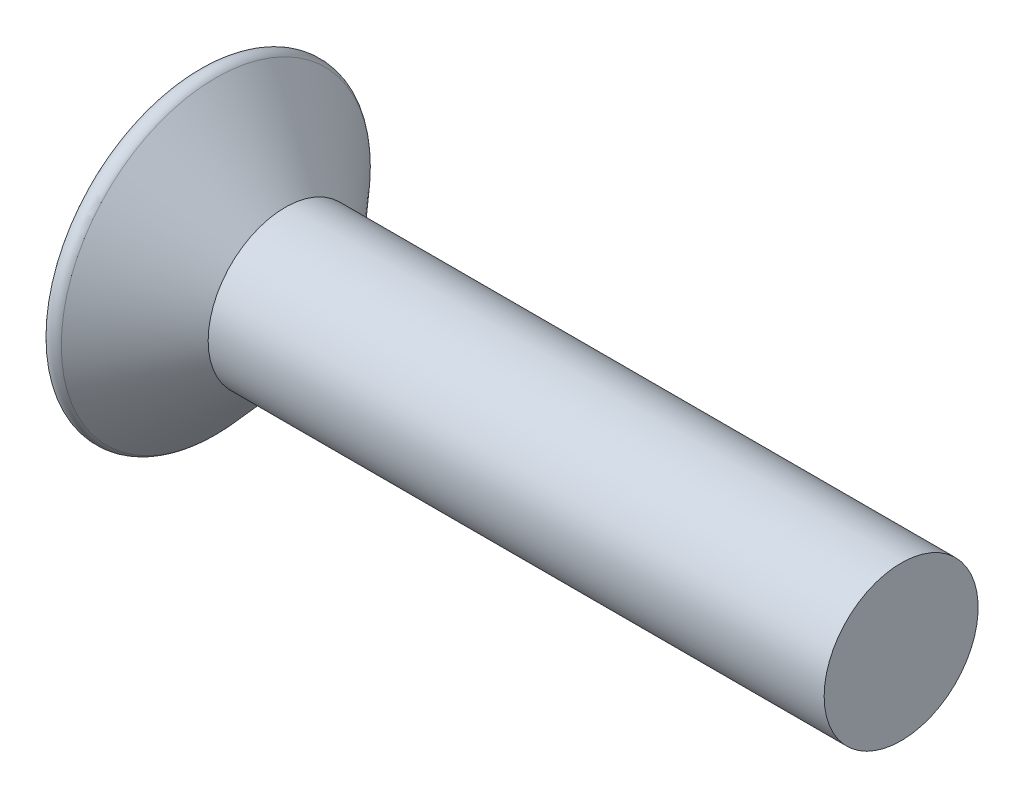
SolidWorks part; units mm, degrees
ref_plane "Plan de face" through (0, 0, 0) normal (0, 0, 1) x (1, 0, 0)
ref_plane "Plan de dessus" through (0, 0, 0) normal (0, 1, 0) x (1, 0, 0)
ref_plane "Plan de droite" through (0, 0, 0) normal (1, 0, 0) x (0, 0, -1)
sketch "Esquisse1" plane through (0, 0, 0) normal (0, 0, 1) x (1, 0, 0)
  line L0 (0, 0) -> (47.1404, 0) construction
  line L1 (0, 0) -> (0, 3.4)
  line L2 (0, 3.4) -> (1.7, 1.5)
  line L3 (1.7, 1.5) -> (13.7, 1.5)
  line L4 (13.7, 1.5) -> (13.7, 0)
  line L5 (0, 0) -> (13.7, 0)
  dimension "D1" = 3.4
  dimension "D2" = 1.7
  dimension "D3" = 1.5
  dimension "D4" = 12
revolve "Révolution1" add sketch "Esquisse1" angle 360 about L0
fillet "Congé1" radius 0.2 1 edges at (0, 0, 3.4)
sketch "Esquisse2" plane through (0, 0, 0) normal (-1, 0, 0) x (0, 0, 1)
  line L1 (0.5, -0.866) -> (1, 0)
  line L2 (1, 0) -> (0.5, 0.866)
  line L3 (0.5, 0.866) -> (-0.5, 0.866)
  line L4 (-0.5, 0.866) -> (-1, 0)
  line L5 (-1, 0) -> (-0.5, -0.866)
  line L6 (-0.5, -0.866) -> (0.5, -0.866)
  circle A0 centre (0, 0) radius 0.866 construction
  dimension "D1" = 1
extrude "Enlèv. mat.-Extru.1" cut sketch "Esquisse2" against normal blind 0.2
